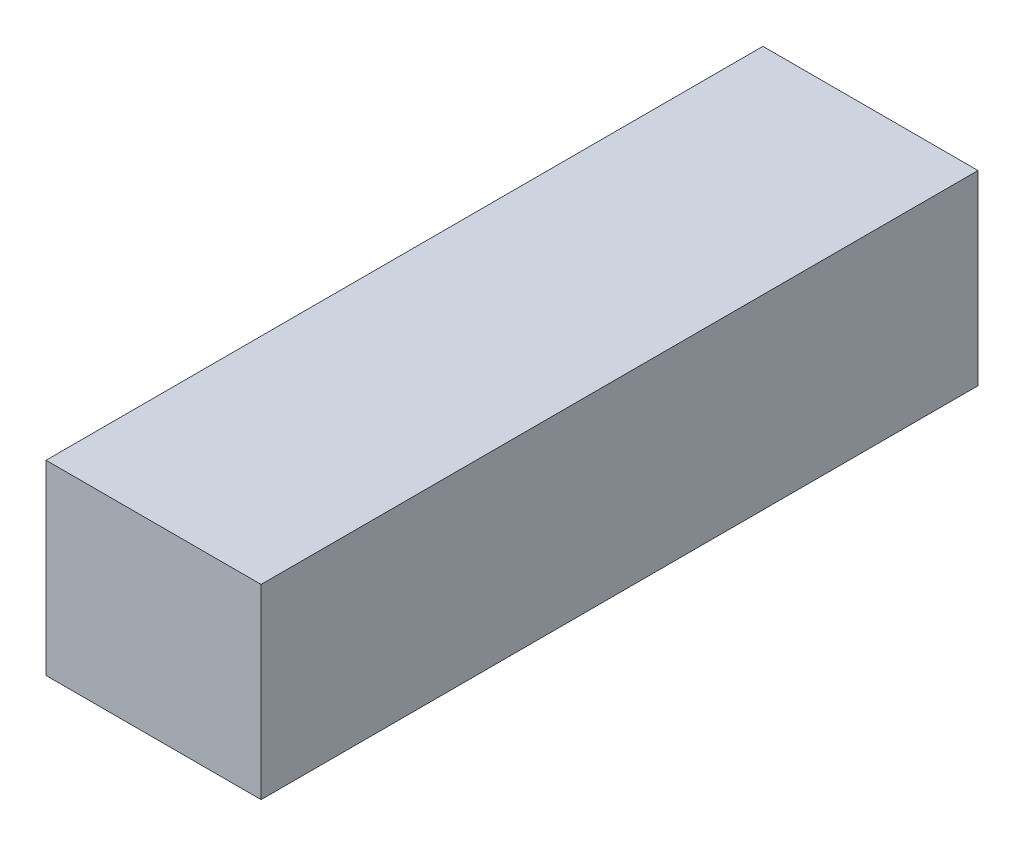
SolidWorks part; units mm, degrees
ref_plane "Front Plane" through (0, 0, 0) normal (0, 0, 1) x (1, 0, 0)
ref_plane "Top Plane" through (0, 0, 0) normal (0, 1, 0) x (1, 0, 0)
ref_plane "Right Plane" through (0, 0, 0) normal (1, 0, 0) x (0, 0, -1)
sketch "Sketch1" plane through (0, 0, 0) normal (0, 1, 0) x (1, 0, 0)
  line L1 (0, 0) -> (30, 0)
  line L2 (0, 0) -> (0, 100)
  line L3 (0, 100) -> (30, 100)
  line L4 (30, 0) -> (30, 100)
  dimension "D1" = 100
  dimension "D2" = 30
extrude "Boss-Extrude1" add sketch "Sketch1" along normal blind 26
